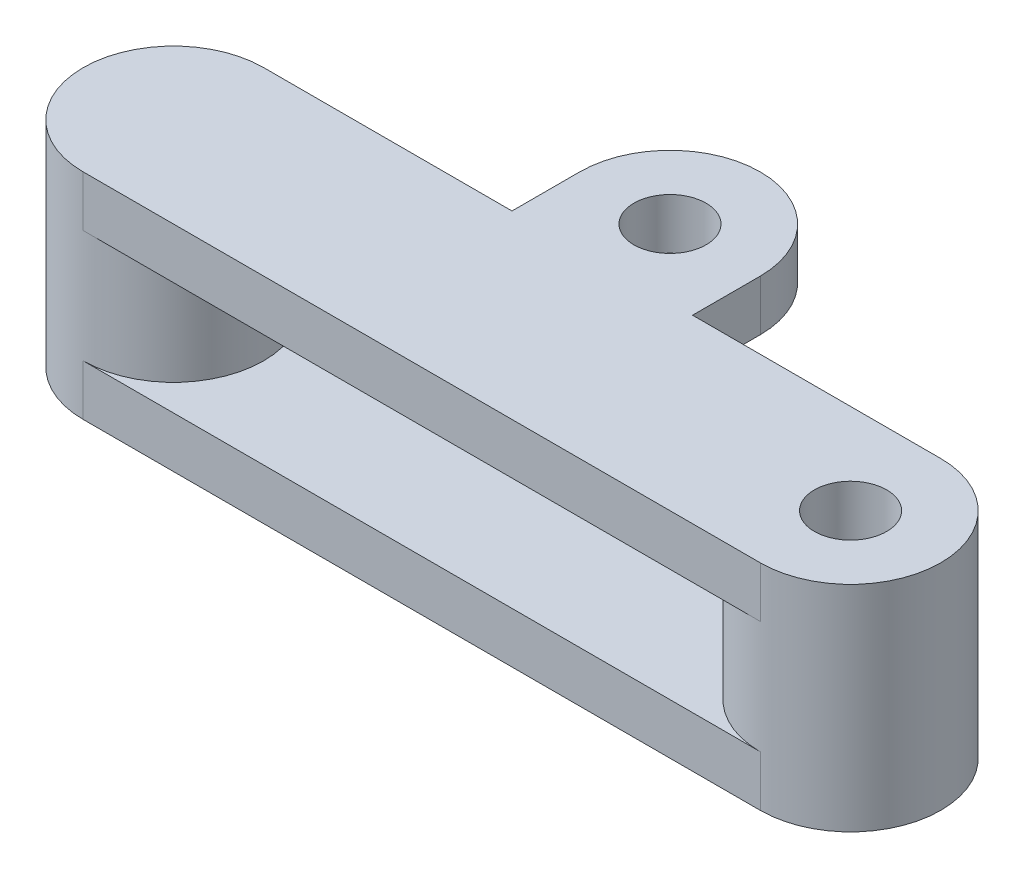
SolidWorks part; units mm, degrees
ref_plane "Front Plane" through (0, 0, 0) normal (0, 0, 1) x (1, 0, 0)
ref_plane "Top Plane" through (0, 0, 0) normal (0, 1, 0) x (1, 0, 0)
ref_plane "Right Plane" through (0, 0, 0) normal (1, 0, 0) x (0, 0, -1)
sketch "Sketch1" plane through (0, 0, 0) normal (0, 1, 0) x (1, 0, 0)
  line L0 (0, 0) -> (-30, 0) construction
  line L1 (0, -4) -> (-30, -4)
  line L2 (0, 4) -> (-11, 4)
  line L3 (-15, 7) -> (-15, 0) construction
  line L4 (-11, 7) -> (-11, 4)
  line L5 (-19, 7) -> (-19, 4)
  line L6 (-19, 4) -> (-30, 4)
  circle A0 centre (0, 0) radius 1.6
  arc A1 (0, -4) -> (0, 4) centre (0, 0) ccw
  arc A2 (-30, 4) -> (-30, -4) centre (-30, 0) ccw
  circle A3 centre (-15, 7) radius 1.6
  arc A4 (-11, 7) -> (-19, 7) centre (-15, 7) ccw
  point P4 (-15, 0)
  point P11 (-15, 0)
  dimension "D1" = 3.2
  dimension "D2" = 4
  dimension "D4" = 4
  dimension "D5" = 3.2
  dimension "D3" = 30
  dimension "D6" = 3
extrude "Boss-Extrude1" add sketch "Sketch1" along normal blind 9.5
ref_plane "Plane1" through (0, 4.75, 0) normal (0, 1, 0) x (1, 0, 0)
sketch "Sketch2" plane through (0, 4.75, 0) normal (0, 1, 0) x (1, 0, 0)
  line L5 (0, 4) -> (-11, 4)
  line L6 (-11, 4) -> (-11, 7)
  line L7 (-19, 7) -> (-19, 4)
  line L8 (-19, 4) -> (-30, 4)
  line L9 (-30, -4) -> (0, -4)
  line L10 (0, 4) -> (-11, 4)
  line L11 (-11, 4) -> (-11, 7)
  line L12 (-19, 7) -> (-19, 4)
  line L13 (-19, 4) -> (-30, 4)
  line L14 (-30, -4) -> (0, -4)
  arc A0 (0, 4) -> (0, -4) centre (0, 0) ccw
  arc A1 (-30, -4) -> (-30, 4) centre (-30, 0) ccw
  arc A5 (0, -4) -> (0, 4) centre (0, 0) ccw
  arc A6 (-11, 7) -> (-19, 7) centre (-15, 7) ccw
  arc A7 (-30, 4) -> (-30, -4) centre (-30, 0) ccw
  arc A9 (-11, 7) -> (-19, 7) centre (-15, 7) ccw
  dimension "D1" = 0
extrude "Cut-Extrude1" cut sketch "Sketch2" against normal blind 2.5 and the other way blind 2.5
